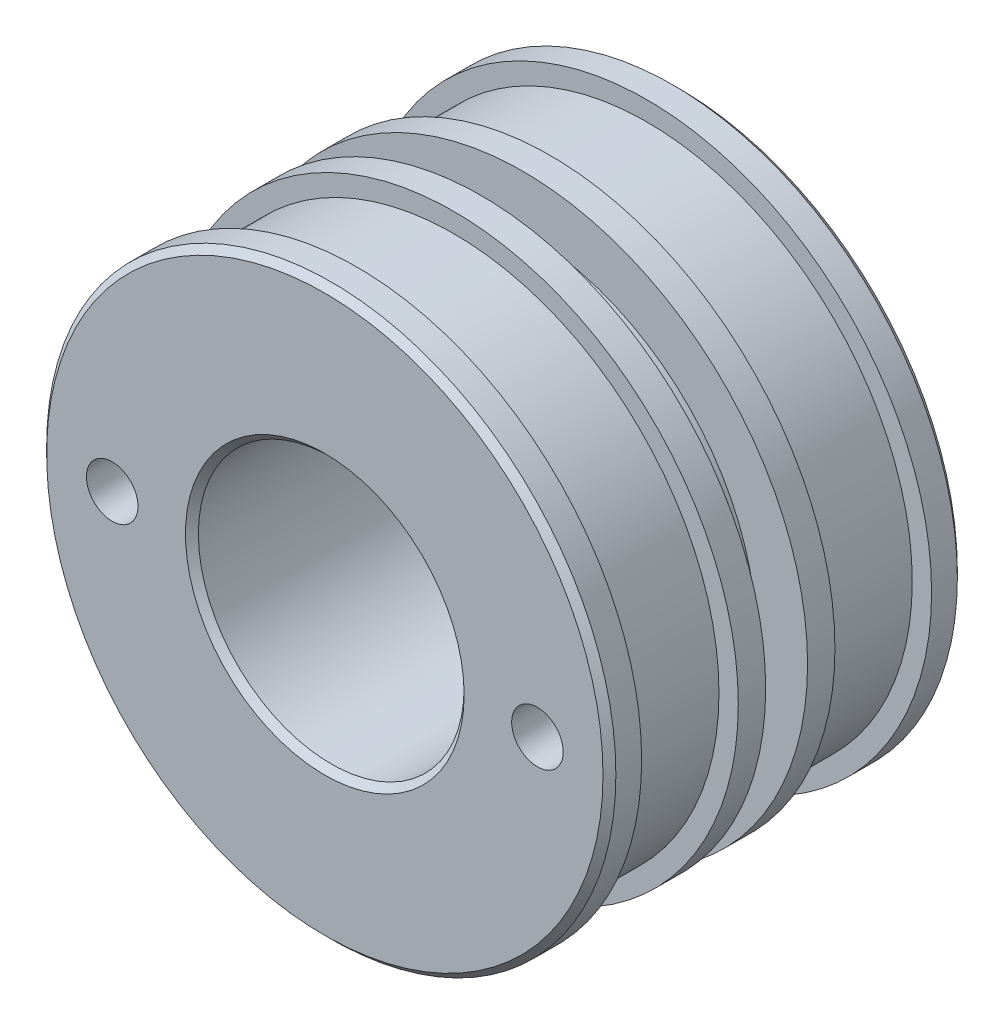
SolidWorks part; units mm, degrees
ref_plane "Płaszczyzna przednia" through (0, 0, 0) normal (0, 0, 1) x (1, 0, 0)
ref_plane "Płaszczyzna górna" through (0, 0, 0) normal (0, 1, 0) x (1, 0, 0)
ref_plane "Płaszczyzna prawa" through (0, 0, 0) normal (1, 0, 0) x (0, 0, -1)
sketch "Szkic1" plane through (0, 0, 0) normal (0, 0, 1) x (1, 0, 0)
  circle A0 centre (0, 0) radius 44.175
  circle A1 centre (0, 0) radius 20.625
  dimension "D1" = 88.35
  dimension "D2" = 41.25
extrude "Dodanie-wyciągnięcie1" add sketch "Szkic1" against normal blind 55
sketch "Szkic2" plane through (0, 0, 0) normal (1, 0, 0) x (0, 0, -1)
  line L0 (0, 0) -> (67.4201, 0) construction
  line L1 (55, 44.175) -> (0, 44.175) construction
  line L2 (5, 44.175) -> (20, 44.175)
  line L3 (5, 44.175) -> (5, 41.175)
  line L4 (5, 41.175) -> (20, 41.175)
  line L5 (20, 44.175) -> (20, 41.175)
  line L6 (0, 44.175) -> (0, -44.175) construction
  line L7 (24.25, 44.175) -> (30.75, 44.175)
  line L8 (24.25, 44.175) -> (24.25, 36.175)
  line L9 (24.25, 36.175) -> (30.75, 36.175)
  line L10 (30.75, 44.175) -> (30.75, 36.175)
  line L11 (35, 44.175) -> (50, 44.175)
  line L12 (35, 44.175) -> (35, 41.175)
  line L13 (35, 41.175) -> (50, 41.175)
  line L14 (50, 44.175) -> (50, 41.175)
  line L15 (55, -44.175) -> (55, 44.175) construction
  dimension "D1" = 5
  dimension "D2" = 3
  dimension "D3" = 15
  dimension "D4" = 6.5
  dimension "D5" = 8
  dimension "D6" = 4.25
  dimension "D7" = 5
revolve "Wycięcie-obrót1" cut sketch "Szkic2" angle 360 about L0
chamfer "Sfazowanie1" distance 1 angle 45 4 edges at (44.175, 0, -55) (20.625, 0, -55) (20.625, 0, 0) (44.175, 0, 0)
sketch "Szkic3" plane through (0, 0, -55) normal (0, 0, -1) x (-1, 0, 0)
  circle A0 centre (0, 0) radius 24.5
  dimension "D1" = 49
extrude "Wytnij-wyciągnięcie1" cut sketch "Szkic3" against normal blind 15
chamfer "Sfazowanie2" distance 1 angle 45 1 edges at (-24.5, 0, -55)
sketch "Szkic5" plane through (0, 0, 0) normal (0, 0, 1) x (1, 0, 0)
  circle A0 centre (0, 0) radius 33 construction
  circle A3 centre (-33, 0) radius 4
  circle A4 centre (33, 0) radius 4
  dimension "D1" = 66
  dimension "D2" = 8
extrude "Wytnij-wyciągnięcie2" cut sketch "Szkic5" against normal blind 9
